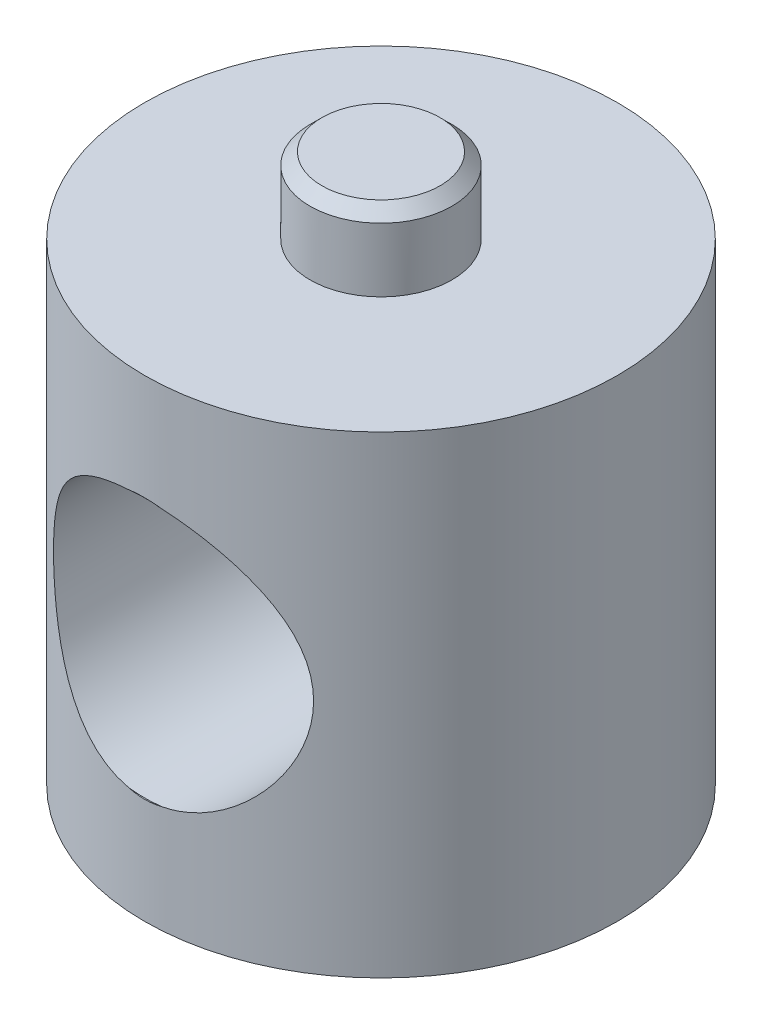
SolidWorks part; units mm, degrees
ref_plane "Piano frontale" through (0, 0, 0) normal (0, 0, 1) x (1, 0, 0)
ref_plane "Piano superiore" through (0, 0, 0) normal (0, 1, 0) x (1, 0, 0)
ref_plane "Piano destro" through (0, 0, 0) normal (1, 0, 0) x (0, 0, -1)
sketch "Schizzo1" plane through (0, 0, 0) normal (0, 1, 0) x (1, 0, 0)
  circle A0 centre (0, 0) radius 10
  dimension "D1" = 20
extrude "Estrusione-Estrusione1" add sketch "Schizzo1" along normal mid plane 20
sketch "Schizzo2" plane through (0, -10, 0) normal (0, -1, 0) x (1, 0, 0)
  circle A0 centre (0, 0) radius 3
  dimension "D1" = 6
extrude "Estrusione-Estrusione2" add sketch "Schizzo2" along normal blind 3.2
mirror "Specchia1" about plane through (0, 0, 0) normal (0, 1, 0) of "Estrusione-Estrusione2"
sketch "Schizzo5" plane through (0, 0, 0) normal (0, 0, 1) x (1, 0, 0)
  point P0 (0, 0)
hole_wizard "Foro per Vite M10-1" positions "Schizzo3D5" profile "Schizzo8" hole size "M10" standard "Ansi Metric"
sketch3d "Schizzo3D5"
  point P0 (0, 0, 0)
  point P3 (0, 0, 0)
  point P5 (0, 0, 0)
  point P7 (0, 0, 0)
  point P9 (0, 0, 10)
  point P12 (0, 0, 0)
sketch "Schizzo8" plane through (0, 0, 10) normal (1, 0, 0) x (0, -1, 0)
  line L0 (0, 0) -> (0, 20)
  line L1 (0, 20) -> (5.5, 20)
  line L2 (5.5, 20) -> (5.5, 0.025)
  line L3 (5.5, 0.025) -> (5.525, 0)
  line L5 (5.525, 0) -> (0, 0)
  line L6 (-5.5, 0.025) -> (-5.525, 0) construction
  line L11 (0, -6.35) -> (0, 107.95) construction
  dimension "Thru Hole Dia." = 11
  dimension "Thru Hole Depth" = 20
  dimension "Near C'Sink Dia." = 11.05
  dimension "Near C'Sink Angle" = 90
chamfer "Smusso1" distance 0.5 angle 45 2 edges at (0, -13.2, -3) (0, 13.2, -3)
